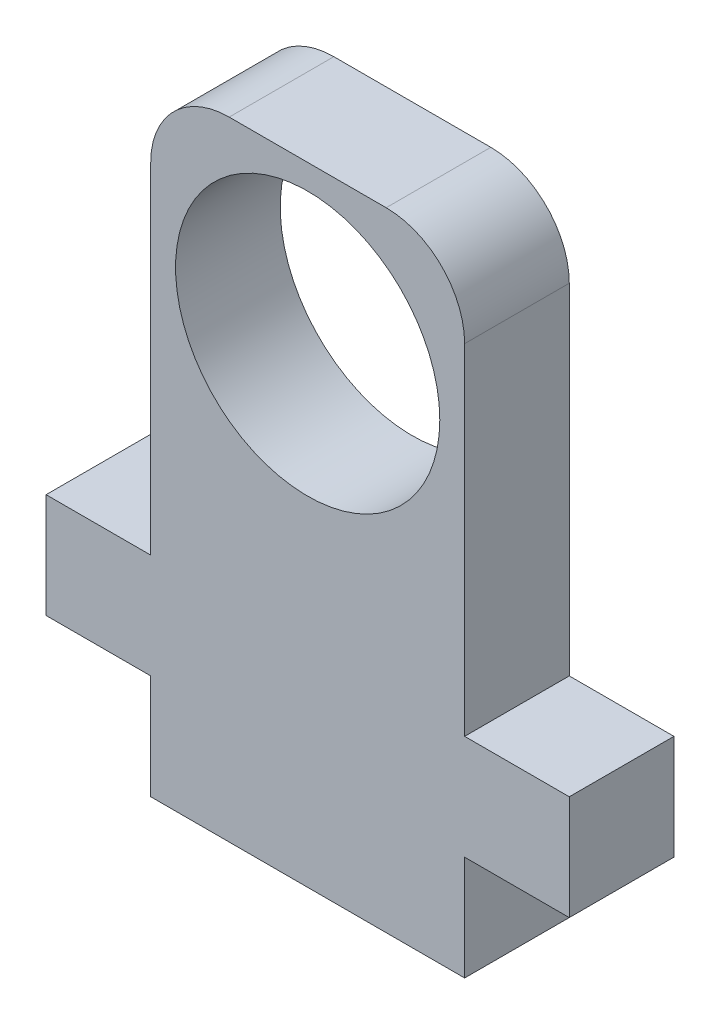
SolidWorks part; units mm, degrees
ref_plane "Спереди" through (0, 0, 0) normal (0, 0, 1) x (1, 0, 0)
ref_plane "Сверху" through (0, 0, 0) normal (0, 1, 0) x (1, 0, 0)
ref_plane "Справа" through (0, 0, 0) normal (1, 0, 0) x (0, 0, -1)
sketch "Эскиз1" plane through (0, 0, 0) normal (0, 0, 1) x (1, 0, 0)
  line L0 (0, 0) -> (0, 4)
  line L1 (0, 4) -> (4, 4)
  line L2 (4, 4) -> (4, 8)
  line L4 (16, 8) -> (16, 4)
  line L5 (16, 4) -> (20, 4)
  line L6 (20, 4) -> (20, 0)
  line L7 (20, 0) -> (16, 0)
  line L8 (16, 0) -> (16, -4)
  line L9 (16, -4) -> (4, -4)
  line L10 (4, -4) -> (4, 0)
  line L11 (4, 0) -> (0, 0)
  line L12 (4, 8) -> (4, 17)
  line L13 (7, 20) -> (13, 20)
  line L14 (16, 17) -> (16, 8)
  circle A0 centre (10, 14) radius 5.05
  arc A1 (13, 20) -> (16, 17) centre (13, 17) cw
  arc A2 (4, 17) -> (7, 20) centre (7, 17) cw
  point P20 (10, 20)
  point P25 (4, 20)
  dimension "D3" = 3
  dimension "D7" = 10.1
  dimension "D1" = 4
  dimension "D2" = 4
  dimension "D4" = 20
  dimension "D5" = 12
  dimension "D6" = 6
extrude "Бобышка-Вытянуть1" add sketch "Эскиз1" along normal blind 4
